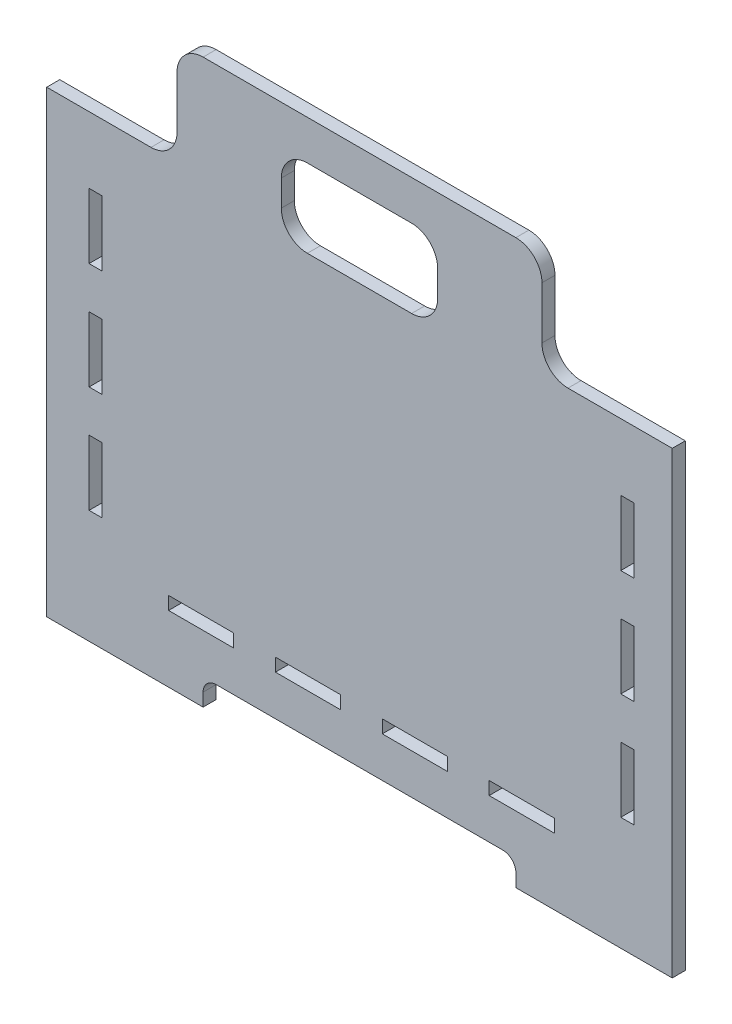
SolidWorks part; units mm, degrees
ref_plane "Front Plane" through (0, 0, 0) normal (0, 0, 1) x (1, 0, 0)
ref_plane "Top Plane" through (0, 0, 0) normal (0, 1, 0) x (1, 0, 0)
ref_plane "Right Plane" through (0, 0, 0) normal (1, 0, 0) x (0, 0, -1)
sketch "Sketch1" plane through (0, 0, 0) normal (0, 0, 1) x (1, 0, 0)
  line L0 (60, -105.6) -> (120, -105.6)
  line L1 (-120, -105.6) -> (-60, -105.6)
  line L2 (-120, -105.6) -> (-120, 70.4)
  line L3 (-70, 110.4) -> (70, 110.4)
  line L4 (120, -105.6) -> (120, 70.4)
  line L5 (-120, -105.6) -> (80, 70.4) construction
  line L6 (-80, 70.4) -> (120, -105.6) construction
  line L9 (120, 70.4) -> (80, 70.4)
  line L10 (70, 110.4) -> (70, 80.4)
  line L13 (-120, 70.4) -> (-80, 70.4)
  line L14 (-70, 110.4) -> (-70, 80.4)
  line L16 (-60, -105.6) -> (-60, -100.6)
  line L17 (-55, -95.6) -> (55, -95.6)
  line L18 (60, -105.6) -> (60, -100.6)
  arc A0 (-80, 70.4) -> (-70, 80.4) centre (-80, 80.4) ccw
  arc A1 (80, 70.4) -> (70, 80.4) centre (80, 80.4) cw
  arc A2 (-60, -100.6) -> (-55, -95.6) centre (-55, -100.6) cw
  arc A3 (55, -95.6) -> (60, -100.6) centre (55, -100.6) cw
  point P0 (0, 0)
  point P18 (-70, 70.4)
  point P21 (70, 70.4)
  point P24 (-60, -95.6)
  point P27 (60, -95.6)
  dimension "D7" = 10
  dimension "D11" = 5
  dimension "D2" = 240
  dimension "D3" = 50
  dimension "D4" = 50
  dimension "D5" = 40
  dimension "D6" = 40
  dimension "D8" = 120
  dimension "D9" = 10
  dimension "D10" = 60
  dimension "D12" = 216
extrude "Boss-Extrude1" add sketch "Sketch1" along normal blind 5
sketch "Sketch2" plane through (0, 0, 5) normal (0, 0, 1) x (1, 0, 0)
  line L0 (120, -105.6) -> (120, 70.4) construction
  line L1 (100.25, 44.91) -> (105.25, 44.91)
  line L2 (100.25, 44.91) -> (100.25, 19.91)
  line L3 (100.25, 19.91) -> (105.25, 19.91)
  line L4 (105.25, 44.91) -> (105.25, 19.91)
  line L5 (100.25, 3.91) -> (105.25, 3.91)
  line L6 (100.25, 3.91) -> (100.25, -21.09)
  line L7 (100.25, -21.09) -> (105.25, -21.09)
  line L8 (105.25, 3.91) -> (105.25, -21.09)
  line L9 (100.25, -37.09) -> (105.25, -37.09)
  line L10 (100.25, -37.09) -> (100.25, -62.09)
  line L11 (100.25, -62.09) -> (105.25, -62.09)
  line L12 (105.25, -37.09) -> (105.25, -62.09)
  line L13 (120, 70.4) -> (80, 70.4) construction
  line L28 (-103.75, 44.91) -> (-98.75, 44.91)
  line L29 (-103.75, 44.91) -> (-103.75, 19.91)
  line L30 (-103.75, 19.91) -> (-98.75, 19.91)
  line L31 (-98.75, 44.91) -> (-98.75, 19.91)
  line L32 (-103.75, 3.91) -> (-98.75, 3.91)
  line L33 (-103.75, 3.91) -> (-103.75, -21.09)
  line L34 (-103.75, -21.09) -> (-98.75, -21.09)
  line L35 (-98.75, 3.91) -> (-98.75, -21.09)
  line L36 (-103.75, -37.09) -> (-98.75, -37.09)
  line L37 (-103.75, -37.09) -> (-103.75, -62.09)
  line L38 (-103.75, -62.09) -> (-98.75, -62.09)
  line L39 (-98.75, -37.09) -> (-98.75, -62.09)
  line L40 (-120, 70.4) -> (-120, -105.6) construction
  point P28 (-101.25, 19.91)
  dimension "D1" = 5
  dimension "D2" = 5
  dimension "D3" = 5
  dimension "D4" = 25
  dimension "D5" = 25
  dimension "D6" = 25
  dimension "D7" = 14.75
  dimension "D8" = 14.75
  dimension "D9" = 14.75
  dimension "D10" = 16
  dimension "D11" = 16
  dimension "D12" = 25.49
  dimension "D13" = 5
  dimension "D14" = 5
  dimension "D15" = 5
  dimension "D16" = 25
  dimension "D17" = 25
  dimension "D18" = 25
  dimension "D19" = 41
  dimension "D20" = 16.25
  dimension "D21" = 16.25
extrude "Cut-Extrude1" cut sketch "Sketch2" against normal through all
fillet "Fillet1" radius 10 2 edges at (-70, 110.4, 2.5) (70, 110.4, 2.5)
sketch "Sketch3" plane through (0, 0, 5) normal (0, 0, 1) x (1, 0, 0)
  line L0 (120, -77.6) -> (100, -77.6) construction
  line L3 (120, -105.6) -> (120, 70.4) construction
  line L4 (-120, -77.6) -> (-99.5, -77.6) construction
  line L8 (-120, 70.4) -> (-120, -105.6) construction
  line L11 (49.75, -75.1) -> (74.75, -75.1)
  line L12 (49.75, -75.1) -> (49.75, -80.1)
  line L13 (49.75, -80.1) -> (74.75, -80.1)
  line L14 (74.75, -75.1) -> (74.75, -80.1)
  line L15 (49.75, -75.1) -> (74.75, -80.1) construction
  line L16 (49.75, -80.1) -> (74.75, -75.1) construction
  line L17 (33.75, -75.1) -> (8.75, -75.1)
  line L18 (33.75, -75.1) -> (33.75, -80.1)
  line L19 (33.75, -80.1) -> (8.75, -80.1)
  line L20 (8.75, -75.1) -> (8.75, -80.1)
  line L21 (33.75, -75.1) -> (8.75, -80.1) construction
  line L22 (33.75, -80.1) -> (8.75, -75.1) construction
  line L23 (-32.25, -75.1) -> (-7.25, -75.1)
  line L24 (-32.25, -75.1) -> (-32.25, -80.1)
  line L25 (-32.25, -80.1) -> (-7.25, -80.1)
  line L26 (-7.25, -75.1) -> (-7.25, -80.1)
  line L27 (-32.25, -75.1) -> (-7.25, -80.1) construction
  line L28 (-32.25, -80.1) -> (-7.25, -75.1) construction
  line L29 (-73.25, -75.1) -> (-48.25, -75.1)
  line L30 (-73.25, -75.1) -> (-73.25, -80.1)
  line L31 (-73.25, -80.1) -> (-48.25, -80.1)
  line L32 (-48.25, -75.1) -> (-48.25, -80.1)
  line L33 (-73.25, -75.1) -> (-48.25, -80.1) construction
  line L34 (-73.25, -80.1) -> (-48.25, -75.1) construction
  line L35 (-120, -105.6) -> (-60, -105.6) construction
  line L37 (60, -105.6) -> (120, -105.6) construction
  point P10 (62.25, -77.6)
  point P16 (21.25, -77.6)
  point P21 (-19.75, -77.6)
  point P26 (-60.75, -77.6)
  point P31 (74.75, -77.6)
  dimension "D2" = 20.5
  dimension "D3" = 28
  dimension "D4" = 25
  dimension "D5" = 25
  dimension "D6" = 25
  dimension "D7" = 25
  dimension "D8" = 16
  dimension "D9" = 16
  dimension "D10" = 16
  dimension "D12" = 25.25
  dimension "D13" = 5
  dimension "D14" = 5
  dimension "D15" = 5
  dimension "D16" = 5
  dimension "D17" = 28
  dimension "D18" = 28
  dimension "D19" = 28
extrude "Cut-Extrude2" cut sketch "Sketch3" against normal blind 10
sketch "Sketch4" plane through (0, 0, 5) normal (0, 0, 1) x (1, 0, 0)
  line L1 (-30, 95.2047) -> (30, 95.2047)
  line L2 (-30, 95.2047) -> (-30, 65.2047)
  line L3 (-30, 65.2047) -> (30, 65.2047)
  line L4 (30, 95.2047) -> (30, 65.2047)
  line L5 (-70, 100.4) -> (-70, 80.4) construction
  dimension "D1" = 60
  dimension "D2" = 30
  dimension "D3" = 40
extrude "Cut-Extrude3" cut sketch "Sketch4" against normal blind 35
fillet "Fillet2" radius 10 4 edges at (30, 65.2047, 2.5) (-30, 65.2047, 2.5) (-30, 95.2047, 2.5) (30, 95.2047, 2.5)
